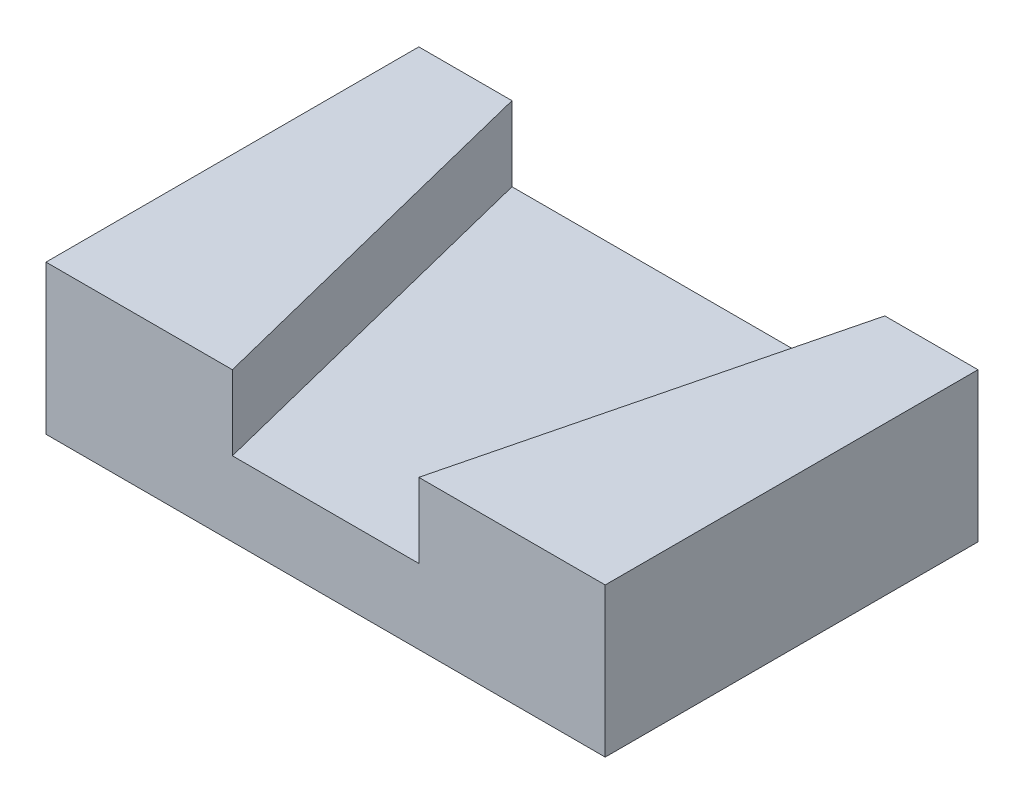
SolidWorks part; units mm, degrees
ref_plane "Front Plane" through (0, 0, 0) normal (0, 0, 1) x (1, 0, 0)
ref_plane "Top Plane" through (0, 0, 0) normal (0, 1, 0) x (1, 0, 0)
ref_plane "Right Plane" through (0, 0, 0) normal (1, 0, 0) x (0, 0, -1)
sketch "Sketch1" plane through (0, 0, 0) normal (0, 1, 0) x (1, 0, 0)
  line L1 (75, -50) -> (-75, -50)
  line L2 (75, -50) -> (75, 50)
  line L3 (75, 50) -> (-75, 50)
  line L4 (-75, -50) -> (-75, 50)
  line L5 (75, -50) -> (-75, 50) construction
  line L6 (75, 50) -> (-75, -50) construction
  point P0 (0, 0)
  dimension "D1" = 150
  dimension "D2" = 100
extrude "Boss-Extrude1" add sketch "Sketch1" along normal blind 40
sketch "Sketch2" plane through (0, 40, 0) normal (0, 1, 0) x (1, 0, 0)
  line L0 (-50, 50) -> (-25, -50)
  line L1 (75, 50) -> (-75, 50) construction
  line L2 (-75, -50) -> (75, -50) construction
  line L3 (-25, -50) -> (25, -50)
  line L4 (25, -50) -> (50, 50)
  line L5 (50, 50) -> (-50, 50)
  line L6 (0, 50) -> (0, -50) construction
  point P10 (50, 50)
  point P11 (0, 50)
  dimension "D1" = 50
  dimension "D2" = 100
extrude "Cut-Extrude1" cut sketch "Sketch2" against normal blind 20
